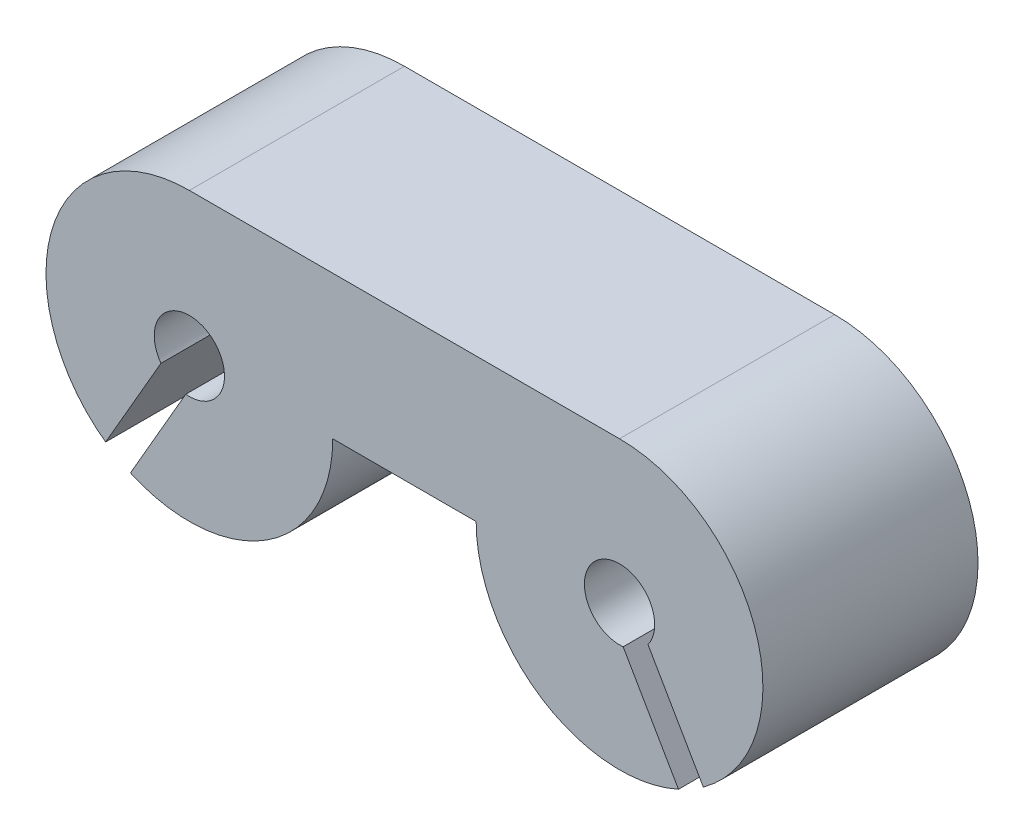
SolidWorks part; units mm, degrees
ref_plane "Front Plane" through (0, 0, 0) normal (0, 0, 1) x (1, 0, 0)
ref_plane "Top Plane" through (0, 0, 0) normal (0, 1, 0) x (1, 0, 0)
ref_plane "Right Plane" through (0, 0, 0) normal (1, 0, 0) x (0, 0, -1)
sketch "Sketch2" plane through (0, 0, 0) normal (0, 0, 1) x (1, 0, 0)
  line L0 (-15, 0) -> (15, 0) construction
  line L1 (-5, 10) -> (-15, 10)
  line L2 (-5, 10) -> (5, 10)
  line L3 (5, 10) -> (15, 10)
  line L4 (-5, 0) -> (5, 0)
  line L5 (-5, 10) -> (-5, 0) construction
  line L6 (5, 0) -> (5, 10) construction
  arc A0 (-15, 10) -> (-5, 0) centre (-15, 0) ccw
  arc A1 (5, 0) -> (15, 10) centre (15, 0) ccw
  arc A2 (-15, 10) -> (-5, 0) centre (-15, 0) cw construction
  arc A3 (15, 10) -> (5, 0) centre (15, 0) ccw construction
  dimension "D1" = 20
  dimension "D2" = 30
  dimension "D3" = 10
extrude "Boss-Extrude1" add sketch "Sketch2" along normal blind 15
sketch "Sketch3" plane through (0, 0, 15) normal (0, 0, 1) x (1, 0, 0)
  circle A0 centre (-15, 0) radius 2.45
  circle A1 centre (15, 0) radius 2.45
  dimension "D1" = 4.9
extrude "Cut-Extrude1" cut sketch "Sketch3" against normal through all
sketch "Sketch4" plane through (0, 0, 15) normal (0, 0, 1) x (1, 0, 0)
  line L0 (-14.134, -0.5) -> (-15.866, 0.5)
  line L1 (-14.134, -0.5) -> (-19.134, -9.1603)
  line L2 (-15.866, 0.5) -> (-20.866, -8.1603)
  line L3 (-19.134, -9.1603) -> (-20.866, -8.1603)
  line L4 (-5, 0) -> (5, 0) construction
  line L5 (14.134, -0.5) -> (15.866, 0.5)
  line L6 (14.134, -0.5) -> (19.134, -9.1603)
  line L7 (15.866, 0.5) -> (20.866, -8.1603)
  line L8 (19.134, -9.1603) -> (20.866, -8.1603)
  arc A0 (-15, 10) -> (-5, 0) centre (-15, 0) ccw construction
  arc A1 (5, 0) -> (15, 10) centre (15, 0) ccw construction
  point P0 (-15, 0)
  point P3 (15, 0)
  dimension "D1" = 2
  dimension "D2" = 120
  dimension "D3" = 120
extrude "Cut-Extrude2" cut sketch "Sketch4" against normal through all
